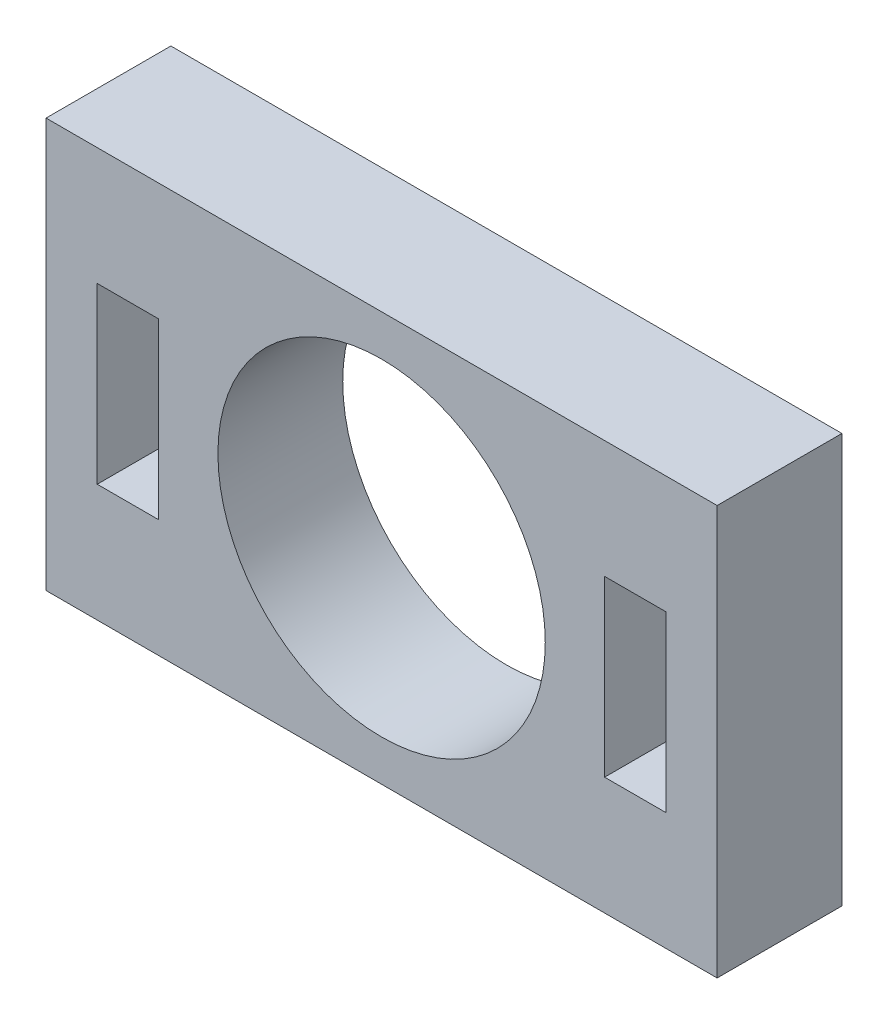
SolidWorks part; units mm, degrees
ref_plane "Front Plane" through (0, 0, 0) normal (0, 0, 1) x (1, 0, 0)
ref_plane "Top Plane" through (0, 0, 0) normal (0, 1, 0) x (1, 0, 0)
ref_plane "Right Plane" through (0, 0, 0) normal (1, 0, 0) x (0, 0, -1)
sketch "Sketch1" plane through (0, 0, 0) normal (0, 0, 1) x (1, 0, 0)
  line L0 (-18.3423, 0) -> (32.7197, 0) construction
  line L1 (-16.4, -10) -> (16.4, -10)
  line L2 (-16.4, -10) -> (-16.4, 10)
  line L3 (-16.4, 10) -> (16.4, 10)
  line L4 (16.4, -10) -> (16.4, 10)
  line L5 (-16.4, -10) -> (16.4, 10) construction
  line L6 (-16.4, 10) -> (16.4, -10) construction
  line L7 (-12.4, 14.3078) -> (-12.4, -16.9608) construction
  line L8 (12.4, 21.468) -> (12.4, -9.8006) construction
  line L10 (10.9, -4.25) -> (13.9, -4.25)
  line L11 (10.9, -4.25) -> (10.9, 4.25)
  line L12 (10.9, 4.25) -> (13.9, 4.25)
  line L13 (13.9, -4.25) -> (13.9, 4.25)
  line L14 (10.9, -4.25) -> (13.9, 4.25) construction
  line L15 (10.9, 4.25) -> (13.9, -4.25) construction
  line L16 (-13.9, -4.25) -> (-10.9, -4.25)
  line L17 (-13.9, -4.25) -> (-13.9, 4.25)
  line L18 (-13.9, 4.25) -> (-10.9, 4.25)
  line L19 (-10.9, -4.25) -> (-10.9, 4.25)
  line L20 (-13.9, -4.25) -> (-10.9, 4.25) construction
  line L21 (-13.9, 4.25) -> (-10.9, -4.25) construction
  circle A0 centre (0, 0) radius 8
  point P0 (0, 0)
  point P14 (12.4, 0)
  point P19 (-12.4, 0)
  dimension "D5" = 16
  dimension "D1" = 20
  dimension "D2" = 32.8
  dimension "D3" = 4
  dimension "D4" = 4
  dimension "D6" = 3
  dimension "D7" = 3
  dimension "D8" = 8.5
  dimension "D9" = 8.5
extrude "Boss-Extrude1" add sketch "Sketch1" along normal blind 6.1
